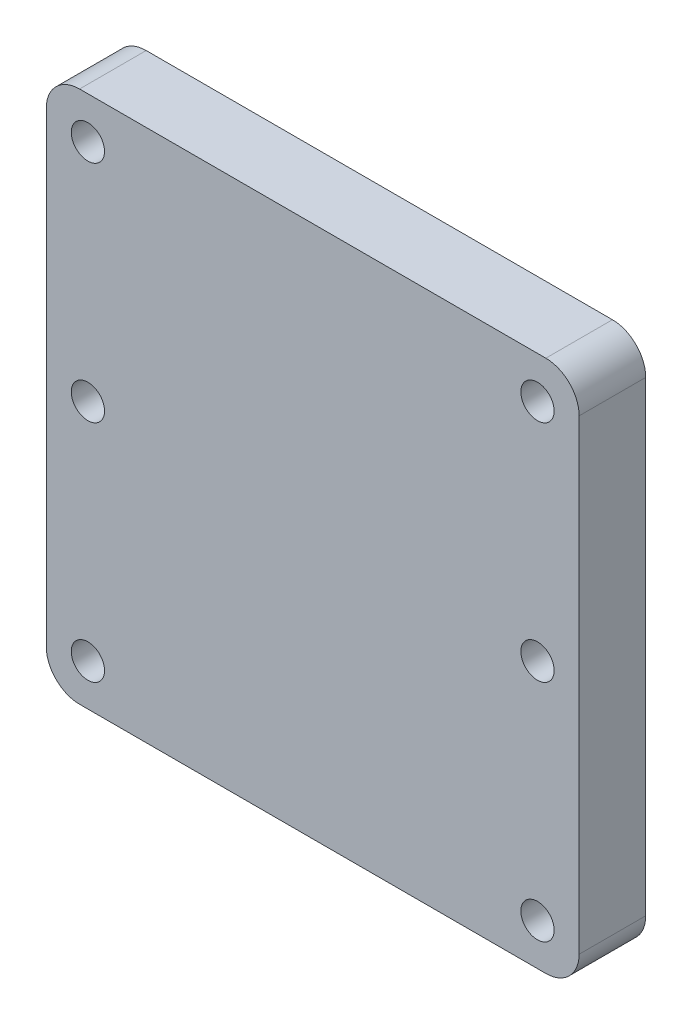
SolidWorks part; units mm, degrees
ref_plane "Front Plane" through (0, 0, 0) normal (0, 0, 1) x (1, 0, 0)
ref_plane "Top Plane" through (0, 0, 0) normal (0, 1, 0) x (1, 0, 0)
ref_plane "Right Plane" through (0, 0, 0) normal (1, 0, 0) x (0, 0, -1)
sketch "Bottom Plate Sketch Profile" plane through (0, 0, 0) normal (0, 0, 1) x (1, 0, 0)
  line L1 (44.45, -50.8) -> (-44.45, -50.8)
  line L2 (50.8, -44.45) -> (50.8, 44.45)
  line L3 (44.45, 50.8) -> (-44.45, 50.8)
  line L4 (-50.8, -44.45) -> (-50.8, 44.45)
  line L5 (50.8, -50.8) -> (-50.8, 50.8) construction
  line L6 (50.8, 50.8) -> (-50.8, -50.8) construction
  line L7 (42.8625, -42.8625) -> (-42.8625, -42.8625) construction
  line L8 (42.8625, -42.8625) -> (42.8625, 42.8625) construction
  line L9 (42.8625, 42.8625) -> (-42.8625, 42.8625) construction
  line L10 (-42.8625, -42.8625) -> (-42.8625, 42.8625) construction
  line L11 (42.8625, -42.8625) -> (-42.8625, 42.8625) construction
  line L12 (42.8625, 42.8625) -> (-42.8625, -42.8625) construction
  circle A0 centre (-42.8625, 42.8625) radius 3.175
  circle A1 centre (42.8625, 42.8625) radius 3.175
  circle A2 centre (42.8625, -42.8625) radius 3.175
  circle A3 centre (-42.8625, -42.8625) radius 3.175
  arc A4 (-44.45, -50.8) -> (-50.8, -44.45) centre (-44.45, -44.45) cw
  arc A5 (44.45, -50.8) -> (50.8, -44.45) centre (44.45, -44.45) ccw
  arc A6 (50.8, 44.45) -> (44.45, 50.8) centre (44.45, 44.45) ccw
  arc A7 (-44.45, 50.8) -> (-50.8, 44.45) centre (-44.45, 44.45) ccw
  circle A8 centre (-42.8625, 0) radius 3.175
  circle A9 centre (42.8625, 0) radius 3.175
  point P0 (0, 0)
  point P6 (0, 0)
  point P31 (-42.8625, 0)
  dimension "D2" = 6.35
  dimension "D4" = 6.35
  dimension "D5" = 6.35
  dimension "D1" = 7.9375
  dimension "D3" = 101.6
extrude "Bottom Plate Extrude" add sketch "Bottom Plate Sketch Profile" along normal blind 12.7
